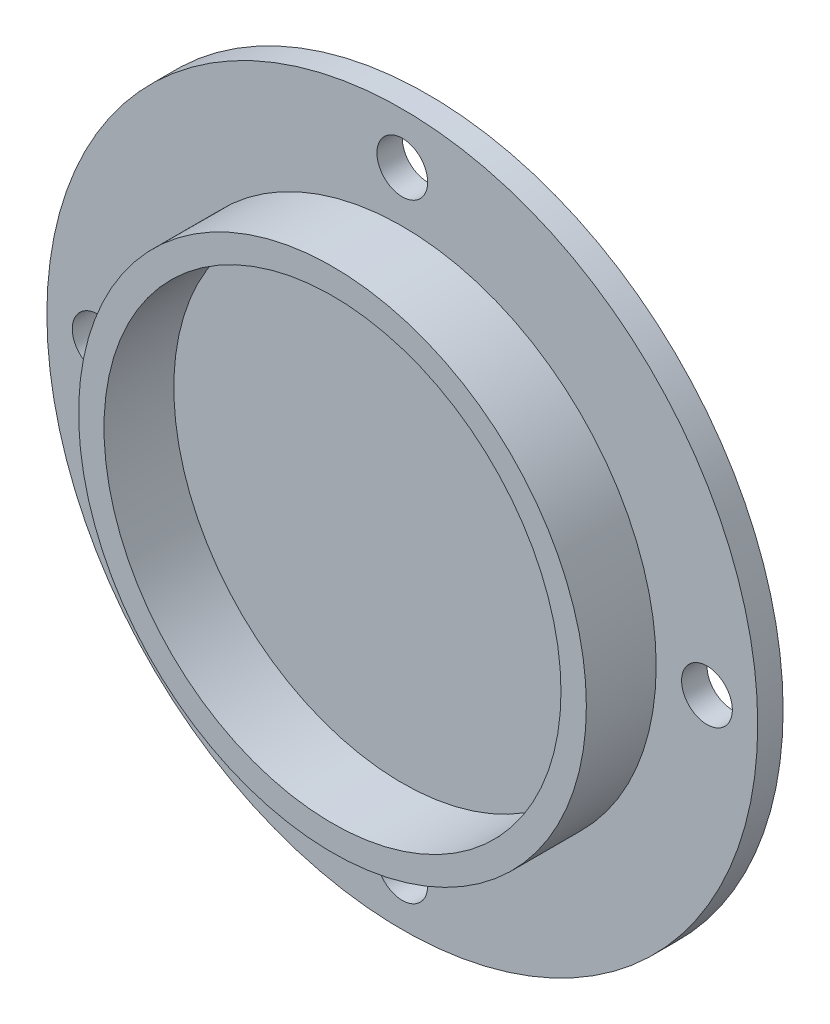
SolidWorks part; units mm, degrees
ref_plane "前视" through (0, 0, 0) normal (0, 0, 1) x (1, 0, 0)
ref_plane "上视" through (0, 0, 0) normal (0, 1, 0) x (1, 0, 0)
ref_plane "右视" through (0, 0, 0) normal (1, 0, 0) x (0, 0, -1)
sketch "草图1" plane through (0, 0, 0) normal (0, 0, 1) x (1, 0, 0)
  line L0 (0, 149.6675) -> (0, -153.1685) construction
  line L1 (-173.2992, 0) -> (179.7177, 0) construction
  circle A0 centre (0, 0) radius 140
  circle A1 centre (0, 0) radius 120 construction
  circle A2 centre (0, 120) radius 10
  circle A3 centre (-120, 0) radius 10
  circle A4 centre (120, 0) radius 10
  circle A5 centre (0, -120) radius 10
  dimension "D1" = 280
  dimension "D2" = 240
  dimension "D3" = 20
  dimension "D4" = 20
  dimension "D5" = 20
  dimension "D6" = 20
extrude "拉伸1" add sketch "草图1" along normal blind 10
sketch "草图2" plane through (0, 0, 10) normal (0, 0, 1) x (1, 0, 0)
  circle A0 centre (0, 0) radius 100
  circle A1 centre (0, 0) radius 90
  dimension "D1" = 200
  dimension "D2" = 180
extrude "拉伸2" add sketch "草图2" along normal blind 27.5
